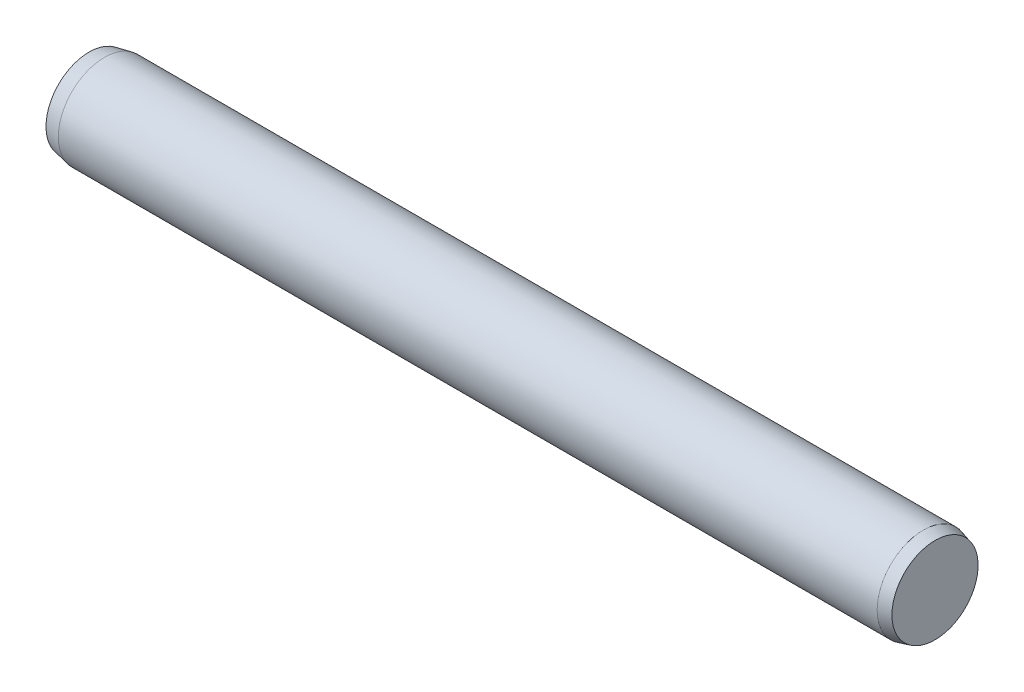
SolidWorks part; units mm, degrees
material "AISI 304"
ref_plane "Front Plane" through (0, 0, 0) normal (0, 0, 1) x (1, 0, 0)
ref_plane "Top Plane" through (0, 0, 0) normal (0, 1, 0) x (1, 0, 0)
ref_plane "Right Plane" through (0, 0, 0) normal (1, 0, 0) x (0, 0, -1)
ref_plane "Plane1" through (0, 0, 0) normal (0, 0, -1) x (-1, 0, 0)
sketch "Sketch1" plane through (0, 0, 0) normal (0, 0, -1) x (-1, 0, 0)
  line L0 (-76.2, 3.2004) -> (-76.2, 0.4004)
  line L1 (-76.2, 0.4004) -> (-21.2, 0.4004)
  line L2 (-21.2, 0.4004) -> (-21.2, 3.2004)
  line L3 (-21.2, 3.2004) -> (-22.2, 3.4004)
  line L4 (-22.2, 3.4004) -> (-75.438, 3.4004)
  line L5 (-75.438, 3.4004) -> (-76.2, 3.2004)
  line L6 (-76.2, 0.4004) -> (-21.2, 0.4004) construction
  dimension "D1" = 0.762
  dimension "D2" = 54
  dimension "D3" = 55
  dimension "D4" = 2.8
  dimension "D5" = 3
revolve "Revolve1" add sketch "Sketch1" angle 360 about L6
